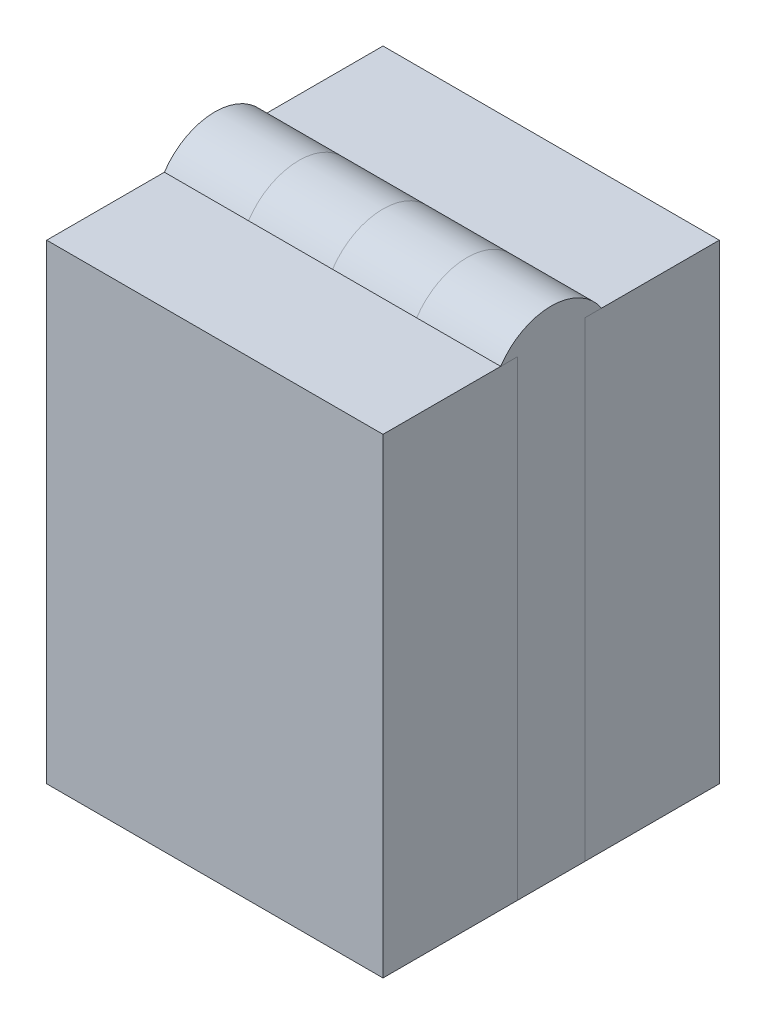
SolidWorks part; units mm, degrees
ref_plane "Front Plane" through (0, 0, 0) normal (0, 0, 1) x (1, 0, 0)
ref_plane "Top Plane" through (0, 0, 0) normal (0, 1, 0) x (1, 0, 0)
ref_plane "Right Plane" through (0, 0, 0) normal (1, 0, 0) x (0, 0, -1)
sketch "Sketch1" plane through (0, 0, 0) normal (1, 0, 0) x (0, 0, -1)
  line L0 (0, 0) -> (0.5, 0) construction
  line L1 (-2.5, -3.5) -> (-0.5, -3.5)
  line L2 (-2.5, -3.5) -> (-2.5, 3.5)
  line L3 (-2.5, 3.5) -> (-0.5, 3.5)
  line L4 (2.5, -3.5) -> (2.5, 3.5)
  line L5 (-2.5, -3.5) -> (2.5, 3.5) construction
  line L6 (-2.5, 3.5) -> (2.5, -3.5) construction
  line L7 (0.5, 3.5) -> (0.5, -3.5)
  line L8 (0, 0) -> (-0.5, 0) construction
  line L9 (-0.5, -3.5) -> (-0.5, 3.5)
  line L10 (0.5, 3.5) -> (2.5, 3.5)
  line L11 (0.5, -3.5) -> (2.5, -3.5)
  line L12 (-0.5, -3.5) -> (0.5, -3.5)
  line L13 (-0.75, 3.5) -> (0.75, 3.5) construction
  arc A1 (-0.75, 3.5) -> (0.75, 3.5) centre (0, 3.0019) cw
  point P0 (0, 0)
  point P16 (0, 3.5)
  dimension "D5" = 1.5
  dimension "D1" = 5
  dimension "D2" = 7
  dimension "D3" = 0.5
  dimension "D4" = 0.5
extrude "Boss-Extrude1" add sketch "Sketch1" along normal blind 5 contours L1 L9 L3 L2 | L7 L11 L4 L10
sketch "Sketch2" plane through (0, 0, 0) normal (-1, 0, 0) x (0, 0, 1)
  line L9 (0.5, -3.5) -> (-0.5, -3.5) construction
  line L10 (-0.5, 3.5) -> (-0.5, -3.5) construction
  line L11 (-0.5, 3.5) -> (-2.5, 3.5) construction
  line L12 (-2.5, -3.5) -> (-2.5, 3.5) construction
  line L13 (-0.5, -3.5) -> (-2.5, -3.5) construction
  line L14 (2.5, -3.5) -> (0.5, -3.5) construction
  line L15 (2.5, -3.5) -> (2.5, 3.5) construction
  line L16 (2.5, 3.5) -> (0.5, 3.5) construction
  line L17 (0.5, -3.5) -> (0.5, 3.5) construction
  line L18 (0.5, -3.5) -> (-0.5, -3.5)
  line L19 (-0.5, 3.5) -> (-0.5, -3.5)
  line L20 (-0.5, 3.5) -> (-2.5, 3.5)
  line L21 (-2.5, -3.5) -> (-2.5, 3.5)
  line L22 (-0.5, -3.5) -> (-2.5, -3.5)
  line L23 (2.5, -3.5) -> (0.5, -3.5)
  line L24 (2.5, -3.5) -> (2.5, 3.5)
  line L25 (2.5, 3.5) -> (0.5, 3.5)
  line L26 (0.5, -3.5) -> (0.5, 3.5)
  arc A1 (0.75, 3.5) -> (-0.75, 3.5) centre (0, 3.0019) ccw construction
  arc A2 (0.75, 3.5) -> (-0.75, 3.5) centre (0, 3.0019) ccw
extrude "Boss-Extrude2" add sketch "Sketch2" against normal blind 1.25 separate body
sketch "Sketch3" plane through (1.25, 0, 0) normal (1, 0, 0) x (0, 0, -1)
  line L5 (-0.75, 3.5) -> (-0.5, 3.5)
  line L6 (-0.75, 3.5) -> (-0.5, 3.5)
  line L7 (-0.5, 3.5) -> (-0.5, -3.5)
  line L8 (0.5, -3.5) -> (0.5, 3.5)
  line L9 (0.5, 3.5) -> (0.75, 3.5)
  line L10 (-0.5, 3.5) -> (-0.5, -3.5)
  line L11 (-0.5, -3.5) -> (0.5, -3.5)
  line L12 (-0.5, -3.5) -> (0.5, -3.5)
  line L13 (0.5, -3.5) -> (0.5, 3.5)
  line L14 (0.5, 3.5) -> (0.75, 3.5)
  arc A1 (0.75, 3.5) -> (-0.75, 3.5) centre (0, 3.0019) ccw
  arc A2 (0.75, 3.5) -> (-0.75, 3.5) centre (0, 3.0019) ccw
  dimension "D1" = 0
extrude "Boss-Extrude3" add sketch "Sketch3" along normal blind 1.25 separate body
sketch "Sketch4" plane through (2.5, 0, 0) normal (1, 0, 0) x (0, 0, -1)
  line L5 (-0.75, 3.5) -> (-0.5, 3.5)
  line L6 (-0.75, 3.5) -> (-0.5, 3.5)
  line L7 (-0.5, 3.5) -> (-0.5, -3.5)
  line L8 (0.5, -3.5) -> (0.5, 3.5)
  line L9 (0.5, 3.5) -> (0.75, 3.5)
  line L10 (-0.5, 3.5) -> (-0.5, -3.5)
  line L11 (-0.5, -3.5) -> (0.5, -3.5)
  line L12 (-0.5, -3.5) -> (0.5, -3.5)
  line L13 (0.5, -3.5) -> (0.5, 3.5)
  line L14 (0.5, 3.5) -> (0.75, 3.5)
  arc A1 (0.75, 3.5) -> (-0.75, 3.5) centre (0, 3.0019) ccw
  arc A2 (0.75, 3.5) -> (-0.75, 3.5) centre (0, 3.0019) ccw
  dimension "D1" = 0
extrude "Boss-Extrude4" add sketch "Sketch4" along normal blind 1.25 separate body
sketch "Sketch5" plane through (3.75, 0, 0) normal (1, 0, 0) x (0, 0, -1)
  line L5 (-0.75, 3.5) -> (-0.5, 3.5)
  line L6 (-0.75, 3.5) -> (-0.5, 3.5)
  line L7 (-0.5, 3.5) -> (-0.5, -3.5)
  line L8 (0.5, -3.5) -> (0.5, 3.5)
  line L9 (0.5, 3.5) -> (0.75, 3.5)
  line L10 (-0.5, 3.5) -> (-0.5, -3.5)
  line L11 (-0.5, -3.5) -> (0.5, -3.5)
  line L12 (-0.5, -3.5) -> (0.5, -3.5)
  line L13 (0.5, -3.5) -> (0.5, 3.5)
  line L14 (0.5, 3.5) -> (0.75, 3.5)
  arc A1 (0.75, 3.5) -> (-0.75, 3.5) centre (0, 3.0019) ccw
  arc A2 (0.75, 3.5) -> (-0.75, 3.5) centre (0, 3.0019) ccw
  dimension "D1" = 0
extrude "Boss-Extrude5" add sketch "Sketch5" along normal blind 1.25 separate body
